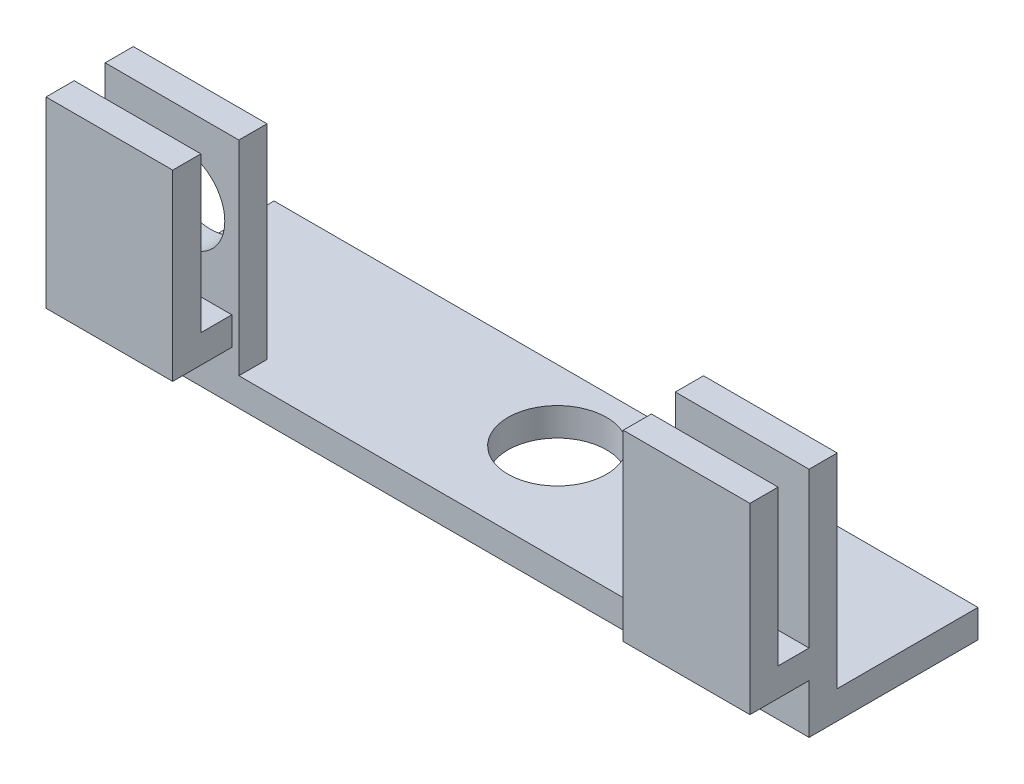
SolidWorks part; units mm, degrees
ref_plane "Plano frontal" through (0, 0, 0) normal (0, 0, 1) x (1, 0, 0)
ref_plane "Plano superior" through (0, 0, 0) normal (0, 1, 0) x (1, 0, 0)
ref_plane "Plano direito" through (0, 0, 0) normal (1, 0, 0) x (0, 0, -1)
sketch "Esboço1" plane through (0, 0, 0) normal (0, 0, 1) x (1, 0, 0)
  line L0 (-2.9307, 5.5815) -> (-2.9307, -2.6685)
  line L1 (-2.9307, -2.6685) -> (22.0693, -2.6685)
  line L2 (22.0693, -2.6685) -> (22.0693, 5.5815)
  line L3 (22.0693, 5.5815) -> (17.3193, 5.5815)
  line L4 (17.3193, 5.5815) -> (17.3193, -1.6685)
  line L5 (17.3193, -1.6685) -> (1.8193, -1.6685)
  line L6 (1.8193, -1.6685) -> (1.8193, 5.5815)
  line L7 (1.8193, 5.5815) -> (-2.9307, 5.5815)
  circle A0 centre (-0.1807, 2.8315) radius 1.5
  circle A1 centre (19.3193, 2.8315) radius 1.5
  dimension "D7" = 2
  dimension "D1" = 1
  dimension "D2" = 8.25
  dimension "D3" = 4.75
  dimension "D4" = 4.75
  dimension "D5" = 8.25
  dimension "D6" = 25
  dimension "D8" = 2.75
  dimension "D9" = 2
extrude "Ressalto-extrusão1" add sketch "Esboço1" along normal blind 1
sketch "Esboço2" plane through (0, 0, 0) normal (0, 0, -1) x (-1, 0, 0)
  line L0 (2.9307, 5.5815) -> (2.9307, -2.6685) construction
  line L1 (-22.0693, -2.6685) -> (2.9307, -2.6685)
  line L2 (-22.0693, -2.6685) -> (-22.0693, -1.6685)
  line L3 (-22.0693, -1.6685) -> (2.9307, -1.6685)
  line L4 (2.9307, -2.6685) -> (2.9307, -1.6685)
extrude "Ressalto-extrusão2" add sketch "Esboço2" along normal blind 5
sketch "Esboço3" plane through (0, -1.6685, 0) normal (0, 1, 0) x (1, 0, 0)
  line L0 (-2.9307, 5) -> (22.0693, 5) construction
  circle A0 centre (9.6279, 2.5) radius 1.75
  dimension "D1" = 3.5
  dimension "D2" = 2.5
extrude "Corte-extrusão1" cut sketch "Esboço3" against normal blind 5
sketch "Esboço4" plane through (0, 0, 1) normal (0, 0, 1) x (1, 0, 0)
  line L0 (1.5693, 0.0815) -> (-2.9307, 0.0815)
  line L2 (-2.9307, 5.5815) -> (-2.9307, -2.6685) construction
  line L3 (-2.9307, 0.0815) -> (-2.9307, -0.9185)
  line L4 (-2.9307, -0.9185) -> (1.5693, -0.9185)
  line L5 (1.5693, -0.9185) -> (1.5693, 0.0815)
  line L6 (1.8193, 5.5815) -> (-2.9307, 5.5815) construction
  line L7 (22.0693, -2.6685) -> (22.0693, 5.5815) construction
  line L8 (22.0693, -0.9185) -> (17.5693, -0.9185)
  line L9 (22.0693, -0.9185) -> (22.0693, 0.0815)
  line L10 (22.0693, 0.0815) -> (17.5693, 0.0815)
  line L11 (17.5693, -0.9185) -> (17.5693, 0.0815)
  line L14 (1.8193, -1.6685) -> (1.8193, 5.5815) construction
  dimension "D1" = 5.5
  dimension "D2" = 1
  dimension "D3" = 0.25
  dimension "D4" = 4.5
extrude "Ressalto-extrusão3" add sketch "Esboço4" along normal blind 1.1
sketch "Esboço5" plane through (0, 0, 2.1) normal (0, 0, 1) x (1, 0, 0)
  line L0 (1.5693, -0.9185) -> (1.5693, 0.0815) construction
  line L1 (-2.9307, -0.9185) -> (1.5693, -0.9185)
  line L2 (-2.9307, -0.9185) -> (-2.9307, 5.5815)
  line L3 (-2.9307, 5.5815) -> (1.5693, 5.5815)
  line L4 (1.5693, -0.9185) -> (1.5693, 5.5815)
  line L5 (17.5693, -0.9185) -> (22.0693, -0.9185)
  line L6 (17.5693, -0.9185) -> (17.5693, 5.5815)
  line L7 (17.5693, 5.5815) -> (22.0693, 5.5815)
  line L8 (22.0693, -0.9185) -> (22.0693, 5.5815)
  line L9 (17.5693, 0.0815) -> (17.5693, -0.9185) construction
extrude "Ressalto-extrusão4" add sketch "Esboço5" along normal blind 1
